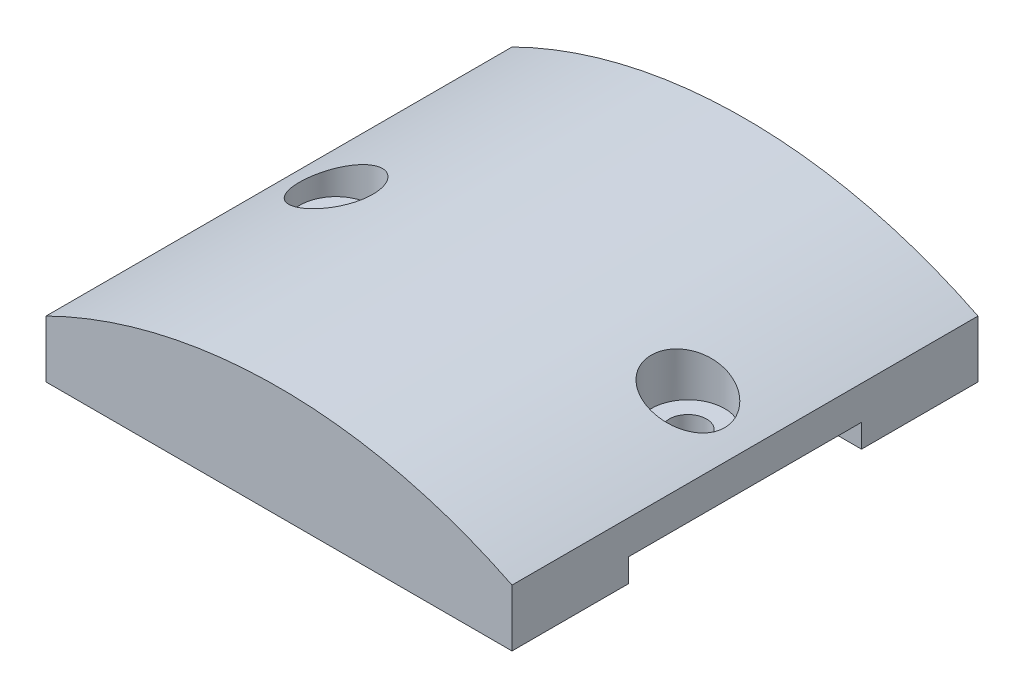
SolidWorks part; units mm, degrees
ref_plane "Plano frontal" through (0, 0, 0) normal (0, 0, 1) x (1, 0, 0)
ref_plane "Plano superior" through (0, 0, 0) normal (0, 1, 0) x (1, 0, 0)
ref_plane "Plano direito" through (0, 0, 0) normal (1, 0, 0) x (0, 0, -1)
sketch "Esboço1" plane through (0, 0, 0) normal (0, 0, 1) x (1, 0, 0)
  line L1 (-20, 40.3113) -> (-20, 37.4113)
  line L2 (-20, 37.4113) -> (20, 37.4113)
  line L3 (20, 37.4113) -> (20, 40.3113)
  arc A0 (20, 40.3113) -> (-20, 40.3113) centre (0, 0) ccw
  dimension "D1" = 90
  dimension "D2" = 40
  dimension "D3" = 2.9
  dimension "D4" = 40.105
extrude "Ressalto-extrusão1" add sketch "Esboço1" along normal blind 40
sketch "Esboço2" plane through (0, 37.4113, 0) normal (0, -1, 0) x (1, 0, 0)
  line L0 (-20, 40) -> (20, 40) construction
  line L1 (20, 40) -> (20, 0) construction
  line L2 (-20, 40) -> (-20, 0) construction
  circle A0 centre (15.1, 20) radius 1.6
  circle A1 centre (-15.1, 20) radius 1.6
  dimension "D1" = 3.2
  dimension "D2" = 3.2
  dimension "D3" = 20
  dimension "D4" = 20
  dimension "D5" = 4.9
  dimension "D6" = 4.9
extrude "Corte-extrusão1" cut sketch "Esboço2" against normal blind 2
sketch "Esboço3" plane through (0, 39.4113, 0) normal (0, -1, 0) x (1, 0, 0)
  circle A0 centre (15.1, 20) radius 3.15
  circle A1 centre (-15.1, 20) radius 3.15
  dimension "D1" = 6.3
  dimension "D2" = 6.3
extrude "Corte-extrusão2" cut sketch "Esboço3" against normal up to surface (2.9796 mm away)
sketch "Esboço4" plane through (0, 37.4113, 0) normal (0, -1, 0) x (1, 0, 0)
  line L0 (20, 40) -> (20, 0) construction
  line L1 (20, 40) -> (-20, 40)
  line L2 (20, 40) -> (20, 30)
  line L3 (20, 30) -> (-20, 30)
  line L4 (-20, 40) -> (-20, 30)
  line L5 (-20, 40) -> (20, 40) construction
  line L6 (-20, 40) -> (-20, 0) construction
  line L8 (20, 0) -> (-20, 0)
  line L9 (20, 0) -> (20, 10)
  line L10 (20, 10) -> (-20, 10)
  line L11 (-20, 0) -> (-20, 10)
  dimension "D1" = 10
  dimension "D2" = 10
extrude "Ressalto-extrusão2" add sketch "Esboço4" along normal blind 2
